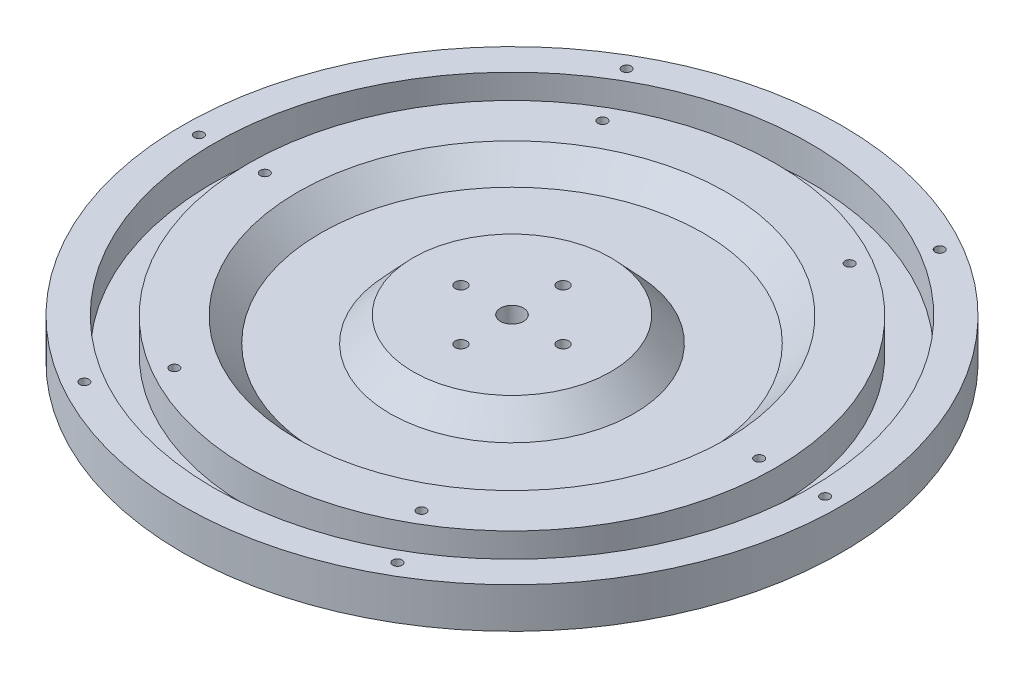
SolidWorks part; units mm, degrees
ref_plane "Ön Düzlem" through (0, 0, 0) normal (0, 0, 1) x (1, 0, 0)
ref_plane "Üst Düzlem" through (0, 0, 0) normal (0, 1, 0) x (1, 0, 0)
ref_plane "Sağ Düzlem" through (0, 0, 0) normal (1, 0, 0) x (0, 0, -1)
sketch "Çizim2" plane through (0, 0, 0) normal (1, 0, 0) x (0, 0, -1)
  line L0 (0, 27.631) -> (0, -32.6549) construction
  line L1 (48.943, 0) -> (-47.5145, 0) construction
  line L2 (0, 0) -> (-100, 0)
  line L3 (-100, 0) -> (-100, 12.25)
  line L4 (-100, 12.25) -> (-90.5, 12.25)
  line L5 (-90.5, 12.25) -> (-90.5, 2)
  line L6 (-90.5, 2) -> (-80, 2)
  line L7 (-80, 2) -> (-80, 12.25)
  line L8 (-80, 12.25) -> (-65, 12.25)
  line L9 (-58, 5) -> (-37, 5)
  line L11 (-65, 12.25) -> (-58, 5)
  line L12 (0, 0) -> (0, 12.5)
  line L13 (0, 12.5) -> (-30, 12.5)
  line L14 (-30, 12.5) -> (-37, 5)
  dimension "D5" = 100
  dimension "D2" = 2
  dimension "D3" = 12.25
  dimension "D4" = 10.25
  dimension "D6" = 15
  dimension "D8" = 9.5
  dimension "D9" = 10.5
revolve "Döndür1" add sketch "Çizim2" angle 360 about L0
sketch "Çizim3" plane through (0, 12.5, 0) normal (0, 1, 0) x (1, 0, 0)
  line L1 (15.5, 0) -> (-15.5, 0) construction
  line L3 (0, 15.5) -> (0, -15.5) construction
  circle A0 centre (0, 0) radius 3.5
  circle A1 centre (-15.5, 0) radius 1.75
  circle A2 centre (0, -15.5) radius 1.75
  circle A3 centre (0, 15.5) radius 1.75
  circle A4 centre (15.5, 0) radius 1.75
  point P16 (0, 0)
extrude "Kes-Ekstrüzyon3" cut sketch "Çizim3" against normal through all both
sketch "Çizim4" plane through (0, 12.5, 0) normal (0, 1, 0) x (1, 0, 0)
  line L0 (0, 0) -> (-75, 0) construction
  line L1 (-75, 0) -> (-95, 0) construction
  circle A0 centre (-75, 0) radius 1.4
  circle A1 centre (-95, 0) radius 1.4
extrude "Kes-Ekstrüzyon4" cut sketch "Çizim4" against normal through all both
pattern_circular "Dairesel Kaplama1" count 6 over 360 about axis through (0, 0, 0) along (0, 1, 0) of "Kes-Ekstrüzyon4"
